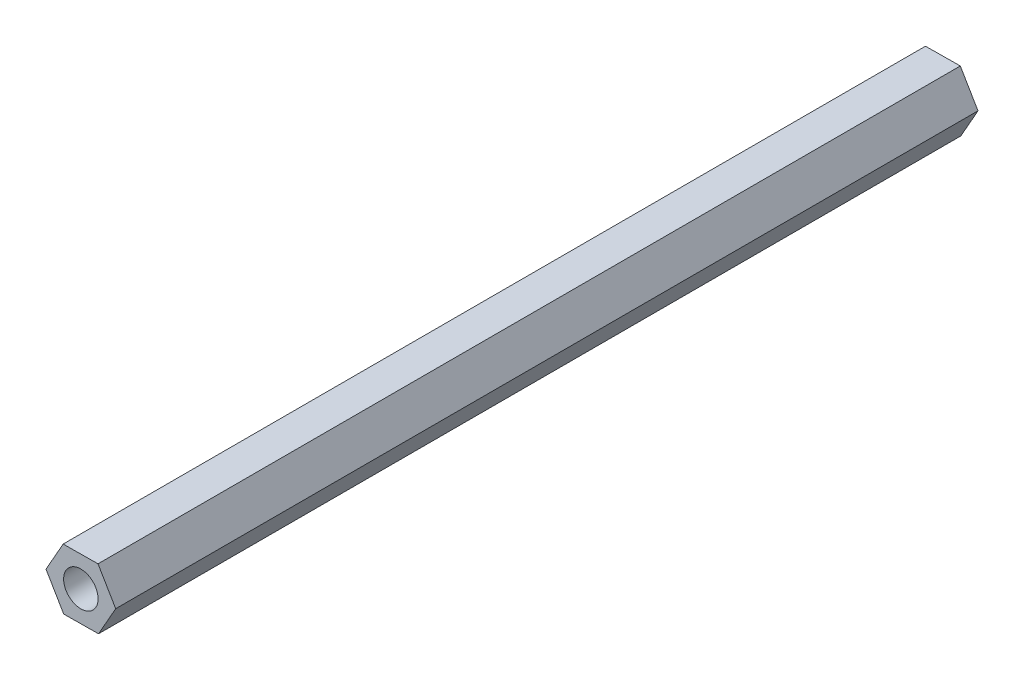
SolidWorks part; units mm, degrees
ref_plane "前视基准面" through (0, 0, 0) normal (0, 0, 1) x (1, 0, 0)
ref_plane "上视基准面" through (0, 0, 0) normal (0, 1, 0) x (1, 0, 0)
ref_plane "右视基准面" through (0, 0, 0) normal (1, 0, 0) x (0, 0, -1)
sketch "草图1" plane through (0, 0, 0) normal (0, 0, 1) x (1, 0, 0)
  line L1 (2.0515, -3.4821) -> (4.0413, 0.0356)
  line L2 (4.0413, 0.0356) -> (1.9898, 3.5177)
  line L3 (1.9898, 3.5177) -> (-2.0515, 3.4821)
  line L4 (-2.0515, 3.4821) -> (-4.0413, -0.0356)
  line L5 (-4.0413, -0.0356) -> (-1.9898, -3.5177)
  line L6 (-1.9898, -3.5177) -> (2.0515, -3.4821)
  circle A0 centre (0, 0) radius 3.5 construction
  circle A1 centre (0, 0) radius 2
extrude "凸台-拉伸1" add sketch "草图1" along normal blind 100
